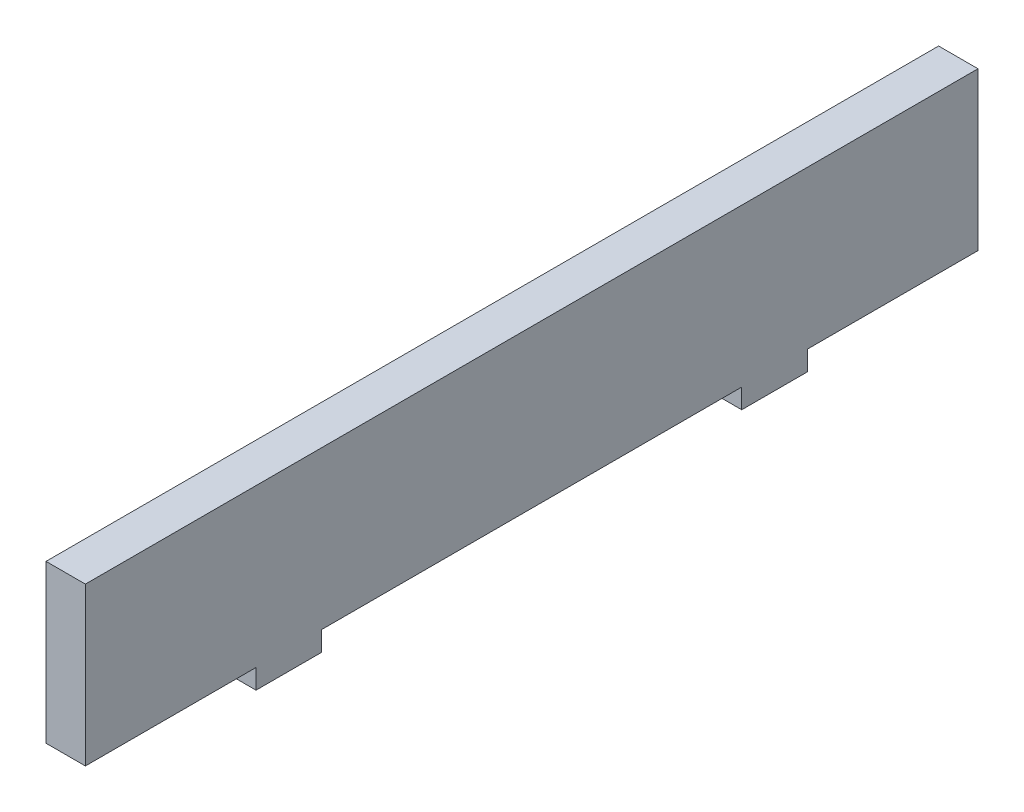
SolidWorks part; units mm, degrees
ref_plane "Plano frontal" through (0, 0, 0) normal (0, 0, 1) x (1, 0, 0)
ref_plane "Plano superior" through (0, 0, 0) normal (0, 1, 0) x (1, 0, 0)
ref_plane "Plano direito" through (0, 0, 0) normal (1, 0, 0) x (0, 0, -1)
sketch "Esboço1" plane through (0, 0, 0) normal (0, 1, 0) x (1, 0, 0)
  line L1 (1.5, -34) -> (-1.5, -34)
  line L2 (1.5, -34) -> (1.5, 34)
  line L3 (1.5, 34) -> (-1.5, 34)
  line L4 (-1.5, -34) -> (-1.5, 34)
  line L5 (1.5, -34) -> (-1.5, 34) construction
  line L6 (1.5, 34) -> (-1.5, -34) construction
  point P0 (0, 0)
  dimension "D1" = 3
  dimension "D2" = 68
extrude "Ressalto-extrusão1" add sketch "Esboço1" along normal blind 12
sketch "Esboço2" plane through (1.5, 0, 0) normal (1, 0, 0) x (0, 0, -1)
  line L0 (0, 0) -> (0, 12) construction
  line L1 (-34, 12) -> (34, 12) construction
  line L2 (-34, 0) -> (34, 0) construction
  line L3 (-21, 0) -> (-16, 0)
  line L4 (-21, 0) -> (-21, -1.5)
  line L5 (-21, -1.5) -> (-16, -1.5)
  line L6 (-16, 0) -> (-16, -1.5)
  line L7 (16, 0) -> (16, -1.5)
  line L8 (21, -1.5) -> (16, -1.5)
  line L9 (21, 0) -> (21, -1.5)
  line L10 (21, 0) -> (16, 0)
  dimension "D1" = 5
  dimension "D2" = 1.5
  dimension "D3" = 16
extrude "Ressalto-extrusão2" add sketch "Esboço2" against normal up to surface (3 mm away) up to face at (-1.5, 6, 0)
